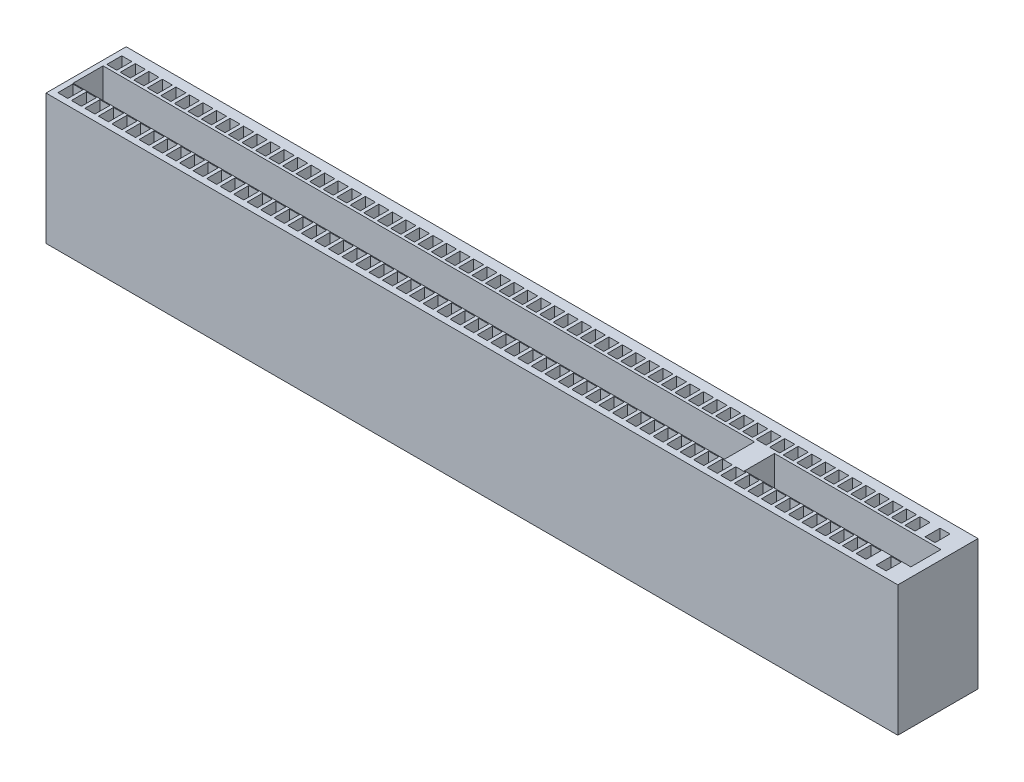
SolidWorks part; units mm, degrees
ref_plane "Front Plane" through (0, 0, 0) normal (0, 0, 1) x (1, 0, 0)
ref_plane "Top Plane" through (0, 0, 0) normal (0, 1, 0) x (1, 0, 0)
ref_plane "Right Plane" through (0, 0, 0) normal (1, 0, 0) x (0, 0, -1)
sketch "Sketch1" plane through (0, 0, 0) normal (0, 1, 0) x (1, 0, 0)
  line L1 (0, 0) -> (85, 0)
  line L2 (0, 0) -> (0, 8)
  line L3 (0, 8) -> (85, 8)
  line L4 (85, 0) -> (85, 8)
  dimension "D1" = 85
  dimension "D2" = 8
extrude "Boss-Extrude1" add sketch "Sketch1" along normal blind 13
sketch "Sketch2" plane through (0, 0, 0) normal (0, -1, 0) x (1, 0, 0)
  line L1 (82.5496, -1.0937) -> (80.0676, -1.0937)
  line L2 (82.5496, -1.0937) -> (82.5496, -3.1244)
  line L3 (82.5496, -3.1244) -> (80.0676, -3.1244)
  line L4 (80.0676, -1.0937) -> (80.0676, -3.1244)
  line L5 (82.5496, -5.2679) -> (80.0676, -5.2679)
  line L6 (82.5496, -5.2679) -> (82.5496, -7.2986)
  line L7 (82.5496, -7.2986) -> (80.0676, -7.2986)
  line L8 (80.0676, -5.2679) -> (80.0676, -7.2986)
  line L9 (5.0452, -1.0937) -> (2.4504, -1.0937)
  line L10 (5.0452, -1.0937) -> (5.0452, -3.9141)
  line L11 (5.0452, -3.9141) -> (2.4504, -3.9141)
  line L12 (2.4504, -1.0937) -> (2.4504, -3.9141)
  line L13 (5.0452, -5.2679) -> (2.4504, -5.2679)
  line L14 (5.0452, -5.2679) -> (5.0452, -7.2986)
  line L15 (5.0452, -7.2986) -> (2.4504, -7.2986)
  line L16 (2.4504, -5.2679) -> (2.4504, -7.2986)
extrude "Boss-Extrude2" add sketch "Sketch2" along normal blind 1 contours L10 L9 L12 L11 | L14 L13 L16 L15 | L2 L1 L4 L3 | L6 L5 L8 L7
sketch "Sketch3" plane through (0, 13, 0) normal (0, 1, 0) x (1, 0, 0)
  line L0 (85, 8) -> (0, 8) construction
  line L1 (0.5, 5.2) -> (65.5, 5.2)
  line L2 (0.5, 5.2) -> (0.5, 2.2)
  line L3 (0.5, 2.2) -> (65.5, 2.2)
  line L4 (65.5, 5.2) -> (65.5, 2.2)
  line L5 (0, 0) -> (85, 0) construction
  line L6 (0, 8) -> (0, 0) construction
  line L7 (84.0994, 5.2) -> (67.5, 5.2)
  line L8 (84.0994, 5.2) -> (84.0994, 2.2)
  line L9 (84.0994, 2.2) -> (67.5, 2.2)
  line L10 (67.5, 5.2) -> (67.5, 2.2)
  line L11 (85, 0) -> (85, 8) construction
  dimension "D1" = 3
  dimension "D2" = 65
  dimension "D3" = 2.8
  dimension "D4" = 2.2
  dimension "D5" = 0.5
  dimension "D6" = 0.9006
  dimension "D7" = 2
  dimension "D8" = 2.8
  dimension "D9" = 2.2
extrude "Cut-Extrude2" cut sketch "Sketch3" against normal blind 10 contours L2 L1 L4 L3 | L8 L7 L10 L9
sketch "Sketch4" plane through (0, 13, 0) normal (0, 1, 0) x (1, 0, 0)
  line L0 (85, 8) -> (0, 8) construction
  line L1 (83.2111, 7) -> (82.2111, 7)
  line L2 (83.2111, 7) -> (83.2111, 5.5)
  line L3 (83.2111, 5.5) -> (82.2111, 5.5)
  line L4 (82.2111, 7) -> (82.2111, 5.5)
  line L5 (81.2111, 7) -> (80.2111, 7)
  line L6 (81.2111, 7) -> (81.2111, 5.5)
  line L7 (81.2111, 5.5) -> (80.2111, 5.5)
  line L8 (80.2111, 7) -> (80.2111, 5.5)
  line L9 (84.0994, 5.2) -> (67.5, 5.2) construction
  line L10 (84.0994, 5.2) -> (67.5, 5.2) construction
  line L11 (-924.5704, 5.5094) -> (49075.4296, 5.5094) construction
  line L12 (79.8611, 7) -> (79.8611, 5.5)
  line L13 (79.8611, 7) -> (78.8611, 7)
  line L14 (78.8611, 7) -> (78.8611, 5.5)
  line L15 (79.8611, 5.5) -> (78.8611, 5.5)
  line L16 (78.5111, 7) -> (78.5111, 5.5)
  line L17 (78.5111, 7) -> (77.5111, 7)
  line L18 (77.5111, 7) -> (77.5111, 5.5)
  line L19 (78.5111, 5.5) -> (77.5111, 5.5)
  line L20 (77.1611, 7) -> (77.1611, 5.5)
  line L21 (77.1611, 7) -> (76.1611, 7)
  line L22 (76.1611, 7) -> (76.1611, 5.5)
  line L23 (77.1611, 5.5) -> (76.1611, 5.5)
  line L24 (75.8111, 7) -> (75.8111, 5.5)
  line L25 (75.8111, 7) -> (74.8111, 7)
  line L26 (74.8111, 7) -> (74.8111, 5.5)
  line L27 (75.8111, 5.5) -> (74.8111, 5.5)
  line L28 (74.4611, 7) -> (74.4611, 5.5)
  line L29 (74.4611, 7) -> (73.4611, 7)
  line L30 (73.4611, 7) -> (73.4611, 5.5)
  line L31 (74.4611, 5.5) -> (73.4611, 5.5)
  line L32 (73.1111, 7) -> (73.1111, 5.5)
  line L33 (73.1111, 7) -> (72.1111, 7)
  line L34 (72.1111, 7) -> (72.1111, 5.5)
  line L35 (73.1111, 5.5) -> (72.1111, 5.5)
  line L36 (71.7611, 7) -> (71.7611, 5.5)
  line L37 (71.7611, 7) -> (70.7611, 7)
  line L38 (70.7611, 7) -> (70.7611, 5.5)
  line L39 (71.7611, 5.5) -> (70.7611, 5.5)
  line L40 (70.4111, 7) -> (70.4111, 5.5)
  line L41 (70.4111, 7) -> (69.4111, 7)
  line L42 (69.4111, 7) -> (69.4111, 5.5)
  line L43 (70.4111, 5.5) -> (69.4111, 5.5)
  line L44 (69.0611, 7) -> (69.0611, 5.5)
  line L45 (69.0611, 7) -> (68.0611, 7)
  line L46 (68.0611, 7) -> (68.0611, 5.5)
  line L47 (69.0611, 5.5) -> (68.0611, 5.5)
  line L48 (67.7111, 7) -> (67.7111, 5.5)
  line L49 (67.7111, 7) -> (66.7111, 7)
  line L50 (66.7111, 7) -> (66.7111, 5.5)
  line L51 (67.7111, 5.5) -> (66.7111, 5.5)
  line L52 (66.3611, 7) -> (66.3611, 5.5)
  line L53 (66.3611, 7) -> (65.3611, 7)
  line L54 (65.3611, 7) -> (65.3611, 5.5)
  line L55 (66.3611, 5.5) -> (65.3611, 5.5)
  line L56 (65.0111, 7) -> (65.0111, 5.5)
  line L57 (65.0111, 7) -> (64.0111, 7)
  line L58 (64.0111, 7) -> (64.0111, 5.5)
  line L59 (65.0111, 5.5) -> (64.0111, 5.5)
  line L60 (63.6611, 7) -> (63.6611, 5.5)
  line L61 (63.6611, 7) -> (62.6611, 7)
  line L62 (62.6611, 7) -> (62.6611, 5.5)
  line L63 (63.6611, 5.5) -> (62.6611, 5.5)
  line L64 (62.3111, 7) -> (62.3111, 5.5)
  line L65 (62.3111, 7) -> (61.3111, 7)
  line L66 (61.3111, 7) -> (61.3111, 5.5)
  line L67 (62.3111, 5.5) -> (61.3111, 5.5)
  line L68 (60.9611, 7) -> (60.9611, 5.5)
  line L69 (60.9611, 7) -> (59.9611, 7)
  line L70 (59.9611, 7) -> (59.9611, 5.5)
  line L71 (60.9611, 5.5) -> (59.9611, 5.5)
  line L72 (59.6111, 7) -> (59.6111, 5.5)
  line L73 (59.6111, 7) -> (58.6111, 7)
  line L74 (58.6111, 7) -> (58.6111, 5.5)
  line L75 (59.6111, 5.5) -> (58.6111, 5.5)
  line L76 (58.2611, 7) -> (58.2611, 5.5)
  line L77 (58.2611, 7) -> (57.2611, 7)
  line L78 (57.2611, 7) -> (57.2611, 5.5)
  line L79 (58.2611, 5.5) -> (57.2611, 5.5)
  line L80 (56.9111, 7) -> (56.9111, 5.5)
  line L81 (56.9111, 7) -> (55.9111, 7)
  line L82 (55.9111, 7) -> (55.9111, 5.5)
  line L83 (56.9111, 5.5) -> (55.9111, 5.5)
  line L84 (55.5611, 7) -> (55.5611, 5.5)
  line L85 (55.5611, 7) -> (54.5611, 7)
  line L86 (54.5611, 7) -> (54.5611, 5.5)
  line L87 (55.5611, 5.5) -> (54.5611, 5.5)
  line L88 (54.2111, 7) -> (54.2111, 5.5)
  line L89 (54.2111, 7) -> (53.2111, 7)
  line L90 (53.2111, 7) -> (53.2111, 5.5)
  line L91 (54.2111, 5.5) -> (53.2111, 5.5)
  line L92 (52.8611, 7) -> (52.8611, 5.5)
  line L93 (52.8611, 7) -> (51.8611, 7)
  line L94 (51.8611, 7) -> (51.8611, 5.5)
  line L95 (52.8611, 5.5) -> (51.8611, 5.5)
  line L96 (51.5111, 7) -> (51.5111, 5.5)
  line L97 (51.5111, 7) -> (50.5111, 7)
  line L98 (50.5111, 7) -> (50.5111, 5.5)
  line L99 (51.5111, 5.5) -> (50.5111, 5.5)
  line L100 (50.1611, 7) -> (50.1611, 5.5)
  line L101 (50.1611, 7) -> (49.1611, 7)
  line L102 (49.1611, 7) -> (49.1611, 5.5)
  line L103 (50.1611, 5.5) -> (49.1611, 5.5)
  line L104 (48.8111, 7) -> (48.8111, 5.5)
  line L105 (48.8111, 7) -> (47.8111, 7)
  line L106 (47.8111, 7) -> (47.8111, 5.5)
  line L107 (48.8111, 5.5) -> (47.8111, 5.5)
  line L108 (47.4611, 7) -> (47.4611, 5.5)
  line L109 (47.4611, 7) -> (46.4611, 7)
  line L110 (46.4611, 7) -> (46.4611, 5.5)
  line L111 (47.4611, 5.5) -> (46.4611, 5.5)
  line L112 (46.1111, 7) -> (46.1111, 5.5)
  line L113 (46.1111, 7) -> (45.1111, 7)
  line L114 (45.1111, 7) -> (45.1111, 5.5)
  line L115 (46.1111, 5.5) -> (45.1111, 5.5)
  line L116 (44.7611, 7) -> (44.7611, 5.5)
  line L117 (44.7611, 7) -> (43.7611, 7)
  line L118 (43.7611, 7) -> (43.7611, 5.5)
  line L119 (44.7611, 5.5) -> (43.7611, 5.5)
  line L120 (43.4111, 7) -> (43.4111, 5.5)
  line L121 (43.4111, 7) -> (42.4111, 7)
  line L122 (42.4111, 7) -> (42.4111, 5.5)
  line L123 (43.4111, 5.5) -> (42.4111, 5.5)
  line L124 (42.0611, 7) -> (42.0611, 5.5)
  line L125 (42.0611, 7) -> (41.0611, 7)
  line L126 (41.0611, 7) -> (41.0611, 5.5)
  line L127 (42.0611, 5.5) -> (41.0611, 5.5)
  line L128 (40.7111, 7) -> (40.7111, 5.5)
  line L129 (40.7111, 7) -> (39.7111, 7)
  line L130 (39.7111, 7) -> (39.7111, 5.5)
  line L131 (40.7111, 5.5) -> (39.7111, 5.5)
  line L132 (39.3611, 7) -> (39.3611, 5.5)
  line L133 (39.3611, 7) -> (38.3611, 7)
  line L134 (38.3611, 7) -> (38.3611, 5.5)
  line L135 (39.3611, 5.5) -> (38.3611, 5.5)
  line L136 (38.0111, 7) -> (38.0111, 5.5)
  line L137 (38.0111, 7) -> (37.0111, 7)
  line L138 (37.0111, 7) -> (37.0111, 5.5)
  line L139 (38.0111, 5.5) -> (37.0111, 5.5)
  line L140 (36.6611, 7) -> (36.6611, 5.5)
  line L141 (36.6611, 7) -> (35.6611, 7)
  line L142 (35.6611, 7) -> (35.6611, 5.5)
  line L143 (36.6611, 5.5) -> (35.6611, 5.5)
  line L144 (35.3111, 7) -> (35.3111, 5.5)
  line L145 (35.3111, 7) -> (34.3111, 7)
  line L146 (34.3111, 7) -> (34.3111, 5.5)
  line L147 (35.3111, 5.5) -> (34.3111, 5.5)
  line L148 (33.9611, 7) -> (33.9611, 5.5)
  line L149 (33.9611, 7) -> (32.9611, 7)
  line L150 (32.9611, 7) -> (32.9611, 5.5)
  line L151 (33.9611, 5.5) -> (32.9611, 5.5)
  line L152 (32.6111, 7) -> (32.6111, 5.5)
  line L153 (32.6111, 7) -> (31.6111, 7)
  line L154 (31.6111, 7) -> (31.6111, 5.5)
  line L155 (32.6111, 5.5) -> (31.6111, 5.5)
  line L156 (31.2611, 7) -> (31.2611, 5.5)
  line L157 (31.2611, 7) -> (30.2611, 7)
  line L158 (30.2611, 7) -> (30.2611, 5.5)
  line L159 (31.2611, 5.5) -> (30.2611, 5.5)
  line L160 (29.9111, 7) -> (29.9111, 5.5)
  line L161 (29.9111, 7) -> (28.9111, 7)
  line L162 (28.9111, 7) -> (28.9111, 5.5)
  line L163 (29.9111, 5.5) -> (28.9111, 5.5)
  line L164 (28.5611, 7) -> (28.5611, 5.5)
  line L165 (28.5611, 7) -> (27.5611, 7)
  line L166 (27.5611, 7) -> (27.5611, 5.5)
  line L167 (28.5611, 5.5) -> (27.5611, 5.5)
  line L168 (27.2111, 7) -> (27.2111, 5.5)
  line L169 (27.2111, 7) -> (26.2111, 7)
  line L170 (26.2111, 7) -> (26.2111, 5.5)
  line L171 (27.2111, 5.5) -> (26.2111, 5.5)
  line L172 (25.8611, 7) -> (25.8611, 5.5)
  line L173 (25.8611, 7) -> (24.8611, 7)
  line L174 (24.8611, 7) -> (24.8611, 5.5)
  line L175 (25.8611, 5.5) -> (24.8611, 5.5)
  line L176 (24.5111, 7) -> (24.5111, 5.5)
  line L177 (24.5111, 7) -> (23.5111, 7)
  line L178 (23.5111, 7) -> (23.5111, 5.5)
  line L179 (24.5111, 5.5) -> (23.5111, 5.5)
  line L180 (23.1611, 7) -> (23.1611, 5.5)
  line L181 (23.1611, 7) -> (22.1611, 7)
  line L182 (22.1611, 7) -> (22.1611, 5.5)
  line L183 (23.1611, 5.5) -> (22.1611, 5.5)
  line L184 (21.8111, 7) -> (21.8111, 5.5)
  line L185 (21.8111, 7) -> (20.8111, 7)
  line L186 (20.8111, 7) -> (20.8111, 5.5)
  line L187 (21.8111, 5.5) -> (20.8111, 5.5)
  line L188 (20.4611, 7) -> (20.4611, 5.5)
  line L189 (20.4611, 7) -> (19.4611, 7)
  line L190 (19.4611, 7) -> (19.4611, 5.5)
  line L191 (20.4611, 5.5) -> (19.4611, 5.5)
  line L192 (19.1111, 7) -> (19.1111, 5.5)
  line L193 (19.1111, 7) -> (18.1111, 7)
  line L194 (18.1111, 7) -> (18.1111, 5.5)
  line L195 (19.1111, 5.5) -> (18.1111, 5.5)
  line L196 (17.7611, 7) -> (17.7611, 5.5)
  line L197 (17.7611, 7) -> (16.7611, 7)
  line L198 (16.7611, 7) -> (16.7611, 5.5)
  line L199 (17.7611, 5.5) -> (16.7611, 5.5)
  line L200 (16.4111, 7) -> (16.4111, 5.5)
  line L201 (16.4111, 7) -> (15.4111, 7)
  line L202 (15.4111, 7) -> (15.4111, 5.5)
  line L203 (16.4111, 5.5) -> (15.4111, 5.5)
  line L204 (15.0611, 7) -> (15.0611, 5.5)
  line L205 (15.0611, 7) -> (14.0611, 7)
  line L206 (14.0611, 7) -> (14.0611, 5.5)
  line L207 (15.0611, 5.5) -> (14.0611, 5.5)
  line L208 (13.7111, 7) -> (13.7111, 5.5)
  line L209 (13.7111, 7) -> (12.7111, 7)
  line L210 (12.7111, 7) -> (12.7111, 5.5)
  line L211 (13.7111, 5.5) -> (12.7111, 5.5)
  line L212 (12.3611, 7) -> (12.3611, 5.5)
  line L213 (12.3611, 7) -> (11.3611, 7)
  line L214 (11.3611, 7) -> (11.3611, 5.5)
  line L215 (12.3611, 5.5) -> (11.3611, 5.5)
  line L216 (11.0111, 7) -> (11.0111, 5.5)
  line L217 (11.0111, 7) -> (10.0111, 7)
  line L218 (10.0111, 7) -> (10.0111, 5.5)
  line L219 (11.0111, 5.5) -> (10.0111, 5.5)
  line L220 (9.6611, 7) -> (9.6611, 5.5)
  line L221 (9.6611, 7) -> (8.6611, 7)
  line L222 (8.6611, 7) -> (8.6611, 5.5)
  line L223 (9.6611, 5.5) -> (8.6611, 5.5)
  line L224 (8.3111, 7) -> (8.3111, 5.5)
  line L225 (8.3111, 7) -> (7.3111, 7)
  line L226 (7.3111, 7) -> (7.3111, 5.5)
  line L227 (8.3111, 5.5) -> (7.3111, 5.5)
  line L228 (6.9611, 7) -> (6.9611, 5.5)
  line L229 (6.9611, 7) -> (5.9611, 7)
  line L230 (5.9611, 7) -> (5.9611, 5.5)
  line L231 (6.9611, 5.5) -> (5.9611, 5.5)
  line L232 (5.6111, 7) -> (5.6111, 5.5)
  line L233 (5.6111, 7) -> (4.6111, 7)
  line L234 (4.6111, 7) -> (4.6111, 5.5)
  line L235 (5.6111, 5.5) -> (4.6111, 5.5)
  line L236 (4.2611, 7) -> (4.2611, 5.5)
  line L237 (4.2611, 7) -> (3.2611, 7)
  line L238 (3.2611, 7) -> (3.2611, 5.5)
  line L239 (4.2611, 5.5) -> (3.2611, 5.5)
  line L240 (2.9111, 7) -> (2.9111, 5.5)
  line L241 (2.9111, 7) -> (1.9111, 7)
  line L242 (1.9111, 7) -> (1.9111, 5.5)
  line L243 (2.9111, 5.5) -> (1.9111, 5.5)
  line L244 (1.5611, 7) -> (1.5611, 5.5)
  line L245 (1.5611, 7) -> (0.5611, 7)
  line L246 (0.5611, 7) -> (0.5611, 5.5)
  line L247 (1.5611, 5.5) -> (0.5611, 5.5)
  line L248 (-991.18, 3.8101) -> (49008.82, 3.8101) construction
  line L249 (-924.5704, 2.1107) -> (49075.4296, 2.1107) construction
  line L250 (1.5611, 2.1201) -> (0.5611, 2.1201)
  line L251 (0.5611, 0.6201) -> (0.5611, 2.1201)
  line L252 (1.5611, 0.6201) -> (0.5611, 0.6201)
  line L253 (1.5611, 0.6201) -> (1.5611, 2.1201)
  line L254 (2.9111, 2.1201) -> (1.9111, 2.1201)
  line L255 (1.9111, 0.6201) -> (1.9111, 2.1201)
  line L256 (2.9111, 0.6201) -> (1.9111, 0.6201)
  line L257 (2.9111, 0.6201) -> (2.9111, 2.1201)
  line L258 (4.2611, 2.1201) -> (3.2611, 2.1201)
  line L259 (3.2611, 0.6201) -> (3.2611, 2.1201)
  line L260 (4.2611, 0.6201) -> (3.2611, 0.6201)
  line L261 (4.2611, 0.6201) -> (4.2611, 2.1201)
  line L262 (5.6111, 2.1201) -> (4.6111, 2.1201)
  line L263 (4.6111, 0.6201) -> (4.6111, 2.1201)
  line L264 (5.6111, 0.6201) -> (4.6111, 0.6201)
  line L265 (5.6111, 0.6201) -> (5.6111, 2.1201)
  line L266 (6.9611, 2.1201) -> (5.9611, 2.1201)
  line L267 (5.9611, 0.6201) -> (5.9611, 2.1201)
  line L268 (6.9611, 0.6201) -> (5.9611, 0.6201)
  line L269 (6.9611, 0.6201) -> (6.9611, 2.1201)
  line L270 (8.3111, 2.1201) -> (7.3111, 2.1201)
  line L271 (7.3111, 0.6201) -> (7.3111, 2.1201)
  line L272 (8.3111, 0.6201) -> (7.3111, 0.6201)
  line L273 (8.3111, 0.6201) -> (8.3111, 2.1201)
  line L274 (9.6611, 2.1201) -> (8.6611, 2.1201)
  line L275 (8.6611, 0.6201) -> (8.6611, 2.1201)
  line L276 (9.6611, 0.6201) -> (8.6611, 0.6201)
  line L277 (9.6611, 0.6201) -> (9.6611, 2.1201)
  line L278 (11.0111, 2.1201) -> (10.0111, 2.1201)
  line L279 (10.0111, 0.6201) -> (10.0111, 2.1201)
  line L280 (11.0111, 0.6201) -> (10.0111, 0.6201)
  line L281 (11.0111, 0.6201) -> (11.0111, 2.1201)
  line L282 (12.3611, 2.1201) -> (11.3611, 2.1201)
  line L283 (11.3611, 0.6201) -> (11.3611, 2.1201)
  line L284 (12.3611, 0.6201) -> (11.3611, 0.6201)
  line L285 (12.3611, 0.6201) -> (12.3611, 2.1201)
  line L286 (13.7111, 2.1201) -> (12.7111, 2.1201)
  line L287 (12.7111, 0.6201) -> (12.7111, 2.1201)
  line L288 (13.7111, 0.6201) -> (12.7111, 0.6201)
  line L289 (13.7111, 0.6201) -> (13.7111, 2.1201)
  line L290 (15.0611, 2.1201) -> (14.0611, 2.1201)
  line L291 (14.0611, 0.6201) -> (14.0611, 2.1201)
  line L292 (15.0611, 0.6201) -> (14.0611, 0.6201)
  line L293 (15.0611, 0.6201) -> (15.0611, 2.1201)
  line L294 (16.4111, 2.1201) -> (15.4111, 2.1201)
  line L295 (15.4111, 0.6201) -> (15.4111, 2.1201)
  line L296 (16.4111, 0.6201) -> (15.4111, 0.6201)
  line L297 (16.4111, 0.6201) -> (16.4111, 2.1201)
  line L298 (17.7611, 2.1201) -> (16.7611, 2.1201)
  line L299 (16.7611, 0.6201) -> (16.7611, 2.1201)
  line L300 (17.7611, 0.6201) -> (16.7611, 0.6201)
  line L301 (17.7611, 0.6201) -> (17.7611, 2.1201)
  line L302 (19.1111, 2.1201) -> (18.1111, 2.1201)
  line L303 (18.1111, 0.6201) -> (18.1111, 2.1201)
  line L304 (19.1111, 0.6201) -> (18.1111, 0.6201)
  line L305 (19.1111, 0.6201) -> (19.1111, 2.1201)
  line L306 (20.4611, 2.1201) -> (19.4611, 2.1201)
  line L307 (19.4611, 0.6201) -> (19.4611, 2.1201)
  line L308 (20.4611, 0.6201) -> (19.4611, 0.6201)
  line L309 (20.4611, 0.6201) -> (20.4611, 2.1201)
  line L310 (21.8111, 2.1201) -> (20.8111, 2.1201)
  line L311 (20.8111, 0.6201) -> (20.8111, 2.1201)
  line L312 (21.8111, 0.6201) -> (20.8111, 0.6201)
  line L313 (21.8111, 0.6201) -> (21.8111, 2.1201)
  line L314 (23.1611, 2.1201) -> (22.1611, 2.1201)
  line L315 (22.1611, 0.6201) -> (22.1611, 2.1201)
  line L316 (23.1611, 0.6201) -> (22.1611, 0.6201)
  line L317 (23.1611, 0.6201) -> (23.1611, 2.1201)
  line L318 (24.5111, 2.1201) -> (23.5111, 2.1201)
  line L319 (23.5111, 0.6201) -> (23.5111, 2.1201)
  line L320 (24.5111, 0.6201) -> (23.5111, 0.6201)
  line L321 (24.5111, 0.6201) -> (24.5111, 2.1201)
  line L322 (25.8611, 2.1201) -> (24.8611, 2.1201)
  line L323 (24.8611, 0.6201) -> (24.8611, 2.1201)
  line L324 (25.8611, 0.6201) -> (24.8611, 0.6201)
  line L325 (25.8611, 0.6201) -> (25.8611, 2.1201)
  line L326 (27.2111, 2.1201) -> (26.2111, 2.1201)
  line L327 (26.2111, 0.6201) -> (26.2111, 2.1201)
  line L328 (27.2111, 0.6201) -> (26.2111, 0.6201)
  line L329 (27.2111, 0.6201) -> (27.2111, 2.1201)
  line L330 (28.5611, 2.1201) -> (27.5611, 2.1201)
  line L331 (27.5611, 0.6201) -> (27.5611, 2.1201)
  line L332 (28.5611, 0.6201) -> (27.5611, 0.6201)
  line L333 (28.5611, 0.6201) -> (28.5611, 2.1201)
  line L334 (29.9111, 2.1201) -> (28.9111, 2.1201)
  line L335 (28.9111, 0.6201) -> (28.9111, 2.1201)
  line L336 (29.9111, 0.6201) -> (28.9111, 0.6201)
  line L337 (29.9111, 0.6201) -> (29.9111, 2.1201)
  line L338 (31.2611, 2.1201) -> (30.2611, 2.1201)
  line L339 (30.2611, 0.6201) -> (30.2611, 2.1201)
  line L340 (31.2611, 0.6201) -> (30.2611, 0.6201)
  line L341 (31.2611, 0.6201) -> (31.2611, 2.1201)
  line L342 (32.6111, 2.1201) -> (31.6111, 2.1201)
  line L343 (31.6111, 0.6201) -> (31.6111, 2.1201)
  line L344 (32.6111, 0.6201) -> (31.6111, 0.6201)
  line L345 (32.6111, 0.6201) -> (32.6111, 2.1201)
  line L346 (33.9611, 2.1201) -> (32.9611, 2.1201)
  line L347 (32.9611, 0.6201) -> (32.9611, 2.1201)
  line L348 (33.9611, 0.6201) -> (32.9611, 0.6201)
  line L349 (33.9611, 0.6201) -> (33.9611, 2.1201)
  line L350 (35.3111, 2.1201) -> (34.3111, 2.1201)
  line L351 (34.3111, 0.6201) -> (34.3111, 2.1201)
  line L352 (35.3111, 0.6201) -> (34.3111, 0.6201)
  line L353 (35.3111, 0.6201) -> (35.3111, 2.1201)
  line L354 (36.6611, 2.1201) -> (35.6611, 2.1201)
  line L355 (35.6611, 0.6201) -> (35.6611, 2.1201)
  line L356 (36.6611, 0.6201) -> (35.6611, 0.6201)
  line L357 (36.6611, 0.6201) -> (36.6611, 2.1201)
  line L358 (38.0111, 2.1201) -> (37.0111, 2.1201)
  line L359 (37.0111, 0.6201) -> (37.0111, 2.1201)
  line L360 (38.0111, 0.6201) -> (37.0111, 0.6201)
  line L361 (38.0111, 0.6201) -> (38.0111, 2.1201)
  line L362 (39.3611, 2.1201) -> (38.3611, 2.1201)
  line L363 (38.3611, 0.6201) -> (38.3611, 2.1201)
  line L364 (39.3611, 0.6201) -> (38.3611, 0.6201)
  line L365 (39.3611, 0.6201) -> (39.3611, 2.1201)
  line L366 (40.7111, 2.1201) -> (39.7111, 2.1201)
  line L367 (39.7111, 0.6201) -> (39.7111, 2.1201)
  line L368 (40.7111, 0.6201) -> (39.7111, 0.6201)
  line L369 (40.7111, 0.6201) -> (40.7111, 2.1201)
  line L370 (42.0611, 2.1201) -> (41.0611, 2.1201)
  line L371 (41.0611, 0.6201) -> (41.0611, 2.1201)
  line L372 (42.0611, 0.6201) -> (41.0611, 0.6201)
  line L373 (42.0611, 0.6201) -> (42.0611, 2.1201)
  line L374 (43.4111, 2.1201) -> (42.4111, 2.1201)
  line L375 (42.4111, 0.6201) -> (42.4111, 2.1201)
  line L376 (43.4111, 0.6201) -> (42.4111, 0.6201)
  line L377 (43.4111, 0.6201) -> (43.4111, 2.1201)
  line L378 (44.7611, 2.1201) -> (43.7611, 2.1201)
  line L379 (43.7611, 0.6201) -> (43.7611, 2.1201)
  line L380 (44.7611, 0.6201) -> (43.7611, 0.6201)
  line L381 (44.7611, 0.6201) -> (44.7611, 2.1201)
  line L382 (46.1111, 2.1201) -> (45.1111, 2.1201)
  line L383 (45.1111, 0.6201) -> (45.1111, 2.1201)
  line L384 (46.1111, 0.6201) -> (45.1111, 0.6201)
  line L385 (46.1111, 0.6201) -> (46.1111, 2.1201)
  line L386 (47.4611, 2.1201) -> (46.4611, 2.1201)
  line L387 (46.4611, 0.6201) -> (46.4611, 2.1201)
  line L388 (47.4611, 0.6201) -> (46.4611, 0.6201)
  line L389 (47.4611, 0.6201) -> (47.4611, 2.1201)
  line L390 (48.8111, 2.1201) -> (47.8111, 2.1201)
  line L391 (47.8111, 0.6201) -> (47.8111, 2.1201)
  line L392 (48.8111, 0.6201) -> (47.8111, 0.6201)
  line L393 (48.8111, 0.6201) -> (48.8111, 2.1201)
  line L394 (50.1611, 2.1201) -> (49.1611, 2.1201)
  line L395 (49.1611, 0.6201) -> (49.1611, 2.1201)
  line L396 (50.1611, 0.6201) -> (49.1611, 0.6201)
  line L397 (50.1611, 0.6201) -> (50.1611, 2.1201)
  line L398 (51.5111, 2.1201) -> (50.5111, 2.1201)
  line L399 (50.5111, 0.6201) -> (50.5111, 2.1201)
  line L400 (51.5111, 0.6201) -> (50.5111, 0.6201)
  line L401 (51.5111, 0.6201) -> (51.5111, 2.1201)
  line L402 (52.8611, 2.1201) -> (51.8611, 2.1201)
  line L403 (51.8611, 0.6201) -> (51.8611, 2.1201)
  line L404 (52.8611, 0.6201) -> (51.8611, 0.6201)
  line L405 (52.8611, 0.6201) -> (52.8611, 2.1201)
  line L406 (54.2111, 2.1201) -> (53.2111, 2.1201)
  line L407 (53.2111, 0.6201) -> (53.2111, 2.1201)
  line L408 (54.2111, 0.6201) -> (53.2111, 0.6201)
  line L409 (54.2111, 0.6201) -> (54.2111, 2.1201)
  line L410 (55.5611, 2.1201) -> (54.5611, 2.1201)
  line L411 (54.5611, 0.6201) -> (54.5611, 2.1201)
  line L412 (55.5611, 0.6201) -> (54.5611, 0.6201)
  line L413 (55.5611, 0.6201) -> (55.5611, 2.1201)
  line L414 (56.9111, 2.1201) -> (55.9111, 2.1201)
  line L415 (55.9111, 0.6201) -> (55.9111, 2.1201)
  line L416 (56.9111, 0.6201) -> (55.9111, 0.6201)
  line L417 (56.9111, 0.6201) -> (56.9111, 2.1201)
  line L418 (58.2611, 2.1201) -> (57.2611, 2.1201)
  line L419 (57.2611, 0.6201) -> (57.2611, 2.1201)
  line L420 (58.2611, 0.6201) -> (57.2611, 0.6201)
  line L421 (58.2611, 0.6201) -> (58.2611, 2.1201)
  line L422 (59.6111, 2.1201) -> (58.6111, 2.1201)
  line L423 (58.6111, 0.6201) -> (58.6111, 2.1201)
  line L424 (59.6111, 0.6201) -> (58.6111, 0.6201)
  line L425 (59.6111, 0.6201) -> (59.6111, 2.1201)
  line L426 (60.9611, 2.1201) -> (59.9611, 2.1201)
  line L427 (59.9611, 0.6201) -> (59.9611, 2.1201)
  line L428 (60.9611, 0.6201) -> (59.9611, 0.6201)
  line L429 (60.9611, 0.6201) -> (60.9611, 2.1201)
  line L430 (62.3111, 2.1201) -> (61.3111, 2.1201)
  line L431 (61.3111, 0.6201) -> (61.3111, 2.1201)
  line L432 (62.3111, 0.6201) -> (61.3111, 0.6201)
  line L433 (62.3111, 0.6201) -> (62.3111, 2.1201)
  line L434 (63.6611, 2.1201) -> (62.6611, 2.1201)
  line L435 (62.6611, 0.6201) -> (62.6611, 2.1201)
  line L436 (63.6611, 0.6201) -> (62.6611, 0.6201)
  line L437 (63.6611, 0.6201) -> (63.6611, 2.1201)
  line L438 (65.0111, 2.1201) -> (64.0111, 2.1201)
  line L439 (64.0111, 0.6201) -> (64.0111, 2.1201)
  line L440 (65.0111, 0.6201) -> (64.0111, 0.6201)
  line L441 (65.0111, 0.6201) -> (65.0111, 2.1201)
  line L442 (66.3611, 2.1201) -> (65.3611, 2.1201)
  line L443 (65.3611, 0.6201) -> (65.3611, 2.1201)
  line L444 (66.3611, 0.6201) -> (65.3611, 0.6201)
  line L445 (66.3611, 0.6201) -> (66.3611, 2.1201)
  line L446 (67.7111, 2.1201) -> (66.7111, 2.1201)
  line L447 (66.7111, 0.6201) -> (66.7111, 2.1201)
  line L448 (67.7111, 0.6201) -> (66.7111, 0.6201)
  line L449 (67.7111, 0.6201) -> (67.7111, 2.1201)
  line L450 (69.0611, 2.1201) -> (68.0611, 2.1201)
  line L451 (68.0611, 0.6201) -> (68.0611, 2.1201)
  line L452 (69.0611, 0.6201) -> (68.0611, 0.6201)
  line L453 (69.0611, 0.6201) -> (69.0611, 2.1201)
  line L454 (70.4111, 2.1201) -> (69.4111, 2.1201)
  line L455 (69.4111, 0.6201) -> (69.4111, 2.1201)
  line L456 (70.4111, 0.6201) -> (69.4111, 0.6201)
  line L457 (70.4111, 0.6201) -> (70.4111, 2.1201)
  line L458 (71.7611, 2.1201) -> (70.7611, 2.1201)
  line L459 (70.7611, 0.6201) -> (70.7611, 2.1201)
  line L460 (71.7611, 0.6201) -> (70.7611, 0.6201)
  line L461 (71.7611, 0.6201) -> (71.7611, 2.1201)
  line L462 (73.1111, 2.1201) -> (72.1111, 2.1201)
  line L463 (72.1111, 0.6201) -> (72.1111, 2.1201)
  line L464 (73.1111, 0.6201) -> (72.1111, 0.6201)
  line L465 (73.1111, 0.6201) -> (73.1111, 2.1201)
  line L466 (74.4611, 2.1201) -> (73.4611, 2.1201)
  line L467 (73.4611, 0.6201) -> (73.4611, 2.1201)
  line L468 (74.4611, 0.6201) -> (73.4611, 0.6201)
  line L469 (74.4611, 0.6201) -> (74.4611, 2.1201)
  line L470 (75.8111, 2.1201) -> (74.8111, 2.1201)
  line L471 (74.8111, 0.6201) -> (74.8111, 2.1201)
  line L472 (75.8111, 0.6201) -> (74.8111, 0.6201)
  line L473 (75.8111, 0.6201) -> (75.8111, 2.1201)
  line L474 (77.1611, 2.1201) -> (76.1611, 2.1201)
  line L475 (76.1611, 0.6201) -> (76.1611, 2.1201)
  line L476 (77.1611, 0.6201) -> (76.1611, 0.6201)
  line L477 (77.1611, 0.6201) -> (77.1611, 2.1201)
  line L478 (78.5111, 2.1201) -> (77.5111, 2.1201)
  line L479 (77.5111, 0.6201) -> (77.5111, 2.1201)
  line L480 (78.5111, 0.6201) -> (77.5111, 0.6201)
  line L481 (78.5111, 0.6201) -> (78.5111, 2.1201)
  line L482 (79.8611, 2.1201) -> (78.8611, 2.1201)
  line L483 (78.8611, 0.6201) -> (78.8611, 2.1201)
  line L484 (79.8611, 0.6201) -> (78.8611, 0.6201)
  line L485 (79.8611, 0.6201) -> (79.8611, 2.1201)
  line L486 (80.2111, 0.6201) -> (80.2111, 2.1201)
  line L487 (81.2111, 2.1201) -> (80.2111, 2.1201)
  line L488 (81.2111, 0.6201) -> (81.2111, 2.1201)
  line L489 (81.2111, 0.6201) -> (80.2111, 0.6201)
  line L490 (82.2111, 0.6201) -> (82.2111, 2.1201)
  line L491 (83.2111, 2.1201) -> (82.2111, 2.1201)
  line L492 (83.2111, 0.6201) -> (83.2111, 2.1201)
  line L493 (83.2111, 0.6201) -> (82.2111, 0.6201)
  point P12 (82.7111, 7)
  dimension "D1" = 1.5
  dimension "D2" = 1
  dimension "D3" = 1
  dimension "D4" = 1.5
  dimension "D5" = 1
  dimension "D6" = 0.3
  dimension "D7" = 1
  dimension "D8" = 0.3
  dimension "D9" = 1
  dimension "D10" = 60
extrude "Cut-Extrude3" cut sketch "Sketch4" against normal blind 10
